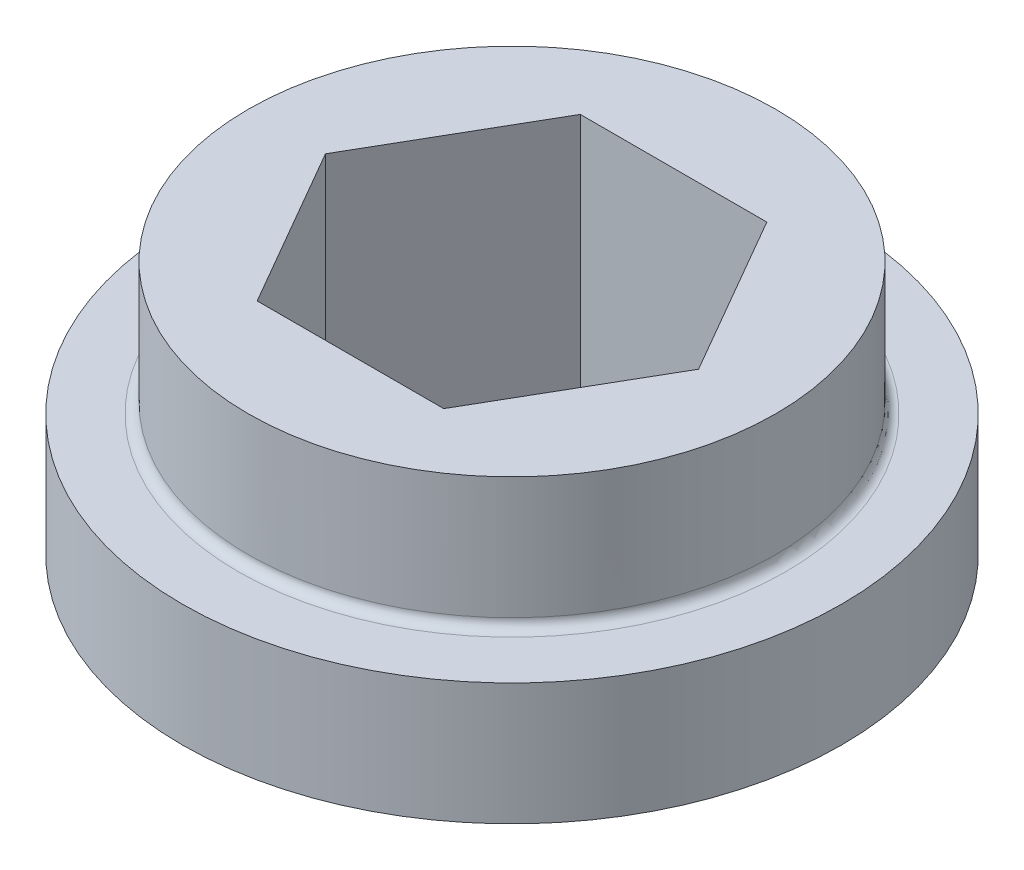
SolidWorks part; units mm, degrees
ref_plane "Front Plane" through (0, 0, 0) normal (0, 0, 1) x (1, 0, 0)
ref_plane "Top Plane" through (0, 0, 0) normal (0, 1, 0) x (1, 0, 0)
ref_plane "Right Plane" through (0, 0, 0) normal (1, 0, 0) x (0, 0, -1)
sketch "Sketch1" plane through (0, 0, 0) normal (0, 1, 0) x (1, 0, 0)
  line L1 (2.829, 0) -> (1.4145, 2.45)
  line L2 (1.4145, 2.45) -> (-1.4145, 2.45)
  line L3 (-1.4145, 2.45) -> (-2.829, 0)
  line L4 (-2.829, 0) -> (-1.4145, -2.45)
  line L5 (-1.4145, -2.45) -> (1.4145, -2.45)
  line L6 (1.4145, -2.45) -> (2.829, 0)
  circle A0 centre (0, 0) radius 4
  circle A1 centre (0, 0) radius 2.45 construction
  dimension "D1" = 4.9
  dimension "D2" = 8
extrude "Boss-Extrude1" add sketch "Sketch1" along normal blind 2
sketch "Sketch2" plane through (0, 0, 0) normal (0, -1, 0) x (1, 0, 0)
  line L1 (2.829, 0) -> (1.4145, 2.45)
  line L2 (1.4145, 2.45) -> (-1.4145, 2.45)
  line L3 (-1.4145, 2.45) -> (-2.829, 0)
  line L4 (-2.829, 0) -> (-1.4145, -2.45)
  line L5 (-1.4145, -2.45) -> (1.4145, -2.45)
  line L6 (1.4145, -2.45) -> (2.829, 0)
  circle A0 centre (0, 0) radius 5
  circle A1 centre (0, 0) radius 2.45 construction
  dimension "D1" = 10
  dimension "D2" = 4.9
extrude "Boss-Extrude2" add sketch "Sketch2" along normal blind 1.85
fillet "Fillet1" radius 0.15 1 edges at (0, 0, 4)
